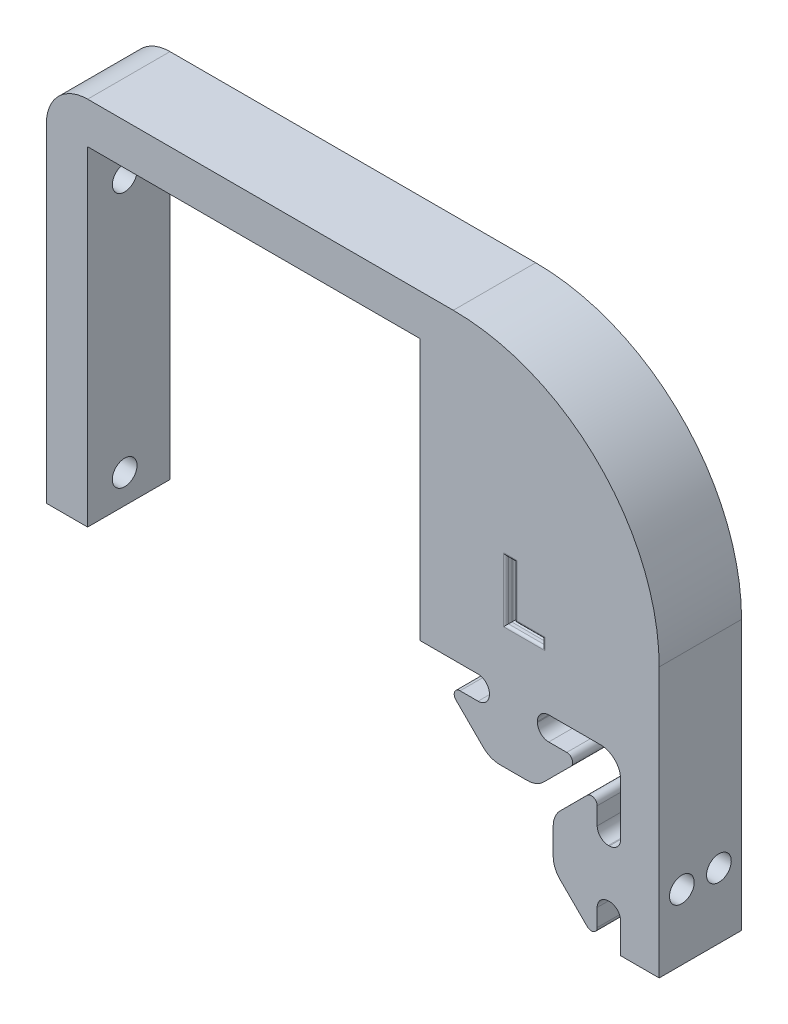
SolidWorks part; units mm, degrees
ref_plane "Front Plane" through (0, 0, 0) normal (0, 0, 1) x (1, 0, 0)
ref_plane "Top Plane" through (0, 0, 0) normal (0, 1, 0) x (1, 0, 0)
ref_plane "Right Plane" through (0, 0, 0) normal (1, 0, 0) x (0, 0, -1)
sketch "Sketch1" plane through (0, 0, 0) normal (0, 0, 1) x (1, 0, 0)
  line L0 (13.02, -7.9417) -> (17.7, -7.9417)
  line L1 (17.7, -7.9417) -> (17.7, 49.77)
  line L2 (17.7, 49.77) -> (-56.7, 49.77)
  line L3 (-14.4742, 2.77) -> (-67.0037, 2.77) construction
  line L4 (-19.4439, 2.77) -> (-19.4439, 44.77) construction
  line L5 (-10.5664, 13.02) -> (-10.5664, 44.77)
  line L6 (-10.5664, 44.77) -> (-51.7, 44.77)
  line L7 (-51.7, 44.77) -> (-51.7, 4.77)
  line L8 (-56.7, 49.77) -> (-56.7, 4.77)
  line L9 (-56.7, 4.77) -> (-51.7, 4.77)
  line L10 (12.7, -6.3331) -> (12.7, -7.9417) construction
  line L11 (13.02, -5.3171) -> (13.02, -4.2875)
  line L12 (11.651, -2.9185) -> (11.5392, -2.9185)
  line L13 (10.1702, -4.2875) -> (10.1702, -6.4021)
  line L14 (8.9631, -6.9029) -> (5.667, -3.6143)
  line L15 (4.8285, -1.5932) -> (4.8285, 1.5932)
  line L16 (5.667, 3.6143) -> (8.9631, 6.9029)
  line L17 (10.1702, 6.4021) -> (10.1702, 4.2875)
  line L18 (11.5392, 2.9185) -> (11.651, 2.9185)
  line L19 (13.02, 10.5773) -> (13.02, 4.2875)
  line L20 (6.3329, 13.02) -> (10.5626, 13.0198)
  line L22 (6.3329, 13.02) -> (4.2875, 13.02)
  line L23 (2.9185, 11.651) -> (2.9185, 11.5392)
  line L24 (4.2875, 10.1702) -> (6.4768, 10.1702)
  line L25 (6.981, 8.9509) -> (3.6723, 5.6497)
  line L26 (1.6558, 4.8158) -> (-1.6558, 4.8158)
  line L27 (-3.6723, 5.6497) -> (-6.981, 8.9509)
  line L28 (-6.4768, 10.1702) -> (-4.2875, 10.1702)
  line L29 (-2.9185, 11.5392) -> (-2.9185, 11.651)
  line L30 (-4.2875, 13.02) -> (-5.3171, 13.02)
  line L31 (-5.3171, 13.02) -> (-10.5664, 13.02)
  line L32 (13.02, -5.3171) -> (13.02, -7.9417)
  line L33 (13.02, -6.3331) -> (13.02, -7.9417) construction
  line L34 (13.02, 4.2875) -> (13.02, 5.3171) construction
  line L37 (5.3171, 13.02) -> (4.2875, 13.02) construction
  line L38 (-6.3331, 13.02) -> (-9.5504, 13.02) construction
  line L96 (12.7, -5.3171) -> (12.7, -4.2875) construction
  line L97 (11.651, -3.2385) -> (11.5392, -3.2385) construction
  line L98 (10.4902, -4.2875) -> (10.4902, -6.4021) construction
  line L99 (8.7371, -7.1294) -> (5.441, -3.8408) construction
  line L100 (4.5085, -1.5932) -> (4.5085, 1.5932) construction
  line L101 (5.441, 3.8408) -> (8.7371, 7.1294) construction
  line L102 (10.4902, 6.4021) -> (10.4902, 4.2875) construction
  line L103 (11.5392, 3.2385) -> (11.651, 3.2385) construction
  line L104 (12.7, 4.2875) -> (12.7, 5.3171) construction
  line L105 (12.7, 6.3331) -> (12.7, 9.5504) construction
  line L106 (9.5504, 12.7) -> (6.3331, 12.7) construction
  line L107 (5.3171, 12.7) -> (4.2875, 12.7) construction
  line L108 (3.2385, 11.651) -> (3.2385, 11.5392) construction
  line L109 (4.2875, 10.4902) -> (6.4768, 10.4902) construction
  line L110 (7.207, 8.7244) -> (3.8983, 5.4232) construction
  line L111 (1.6558, 4.4958) -> (-1.6558, 4.4958) construction
  line L112 (-3.8983, 5.4232) -> (-7.207, 8.7244) construction
  line L113 (-6.4768, 10.4902) -> (-4.2875, 10.4902) construction
  line L114 (-3.2385, 11.5392) -> (-3.2385, 11.651) construction
  line L115 (-4.2875, 12.7) -> (-5.3171, 12.7) construction
  line L116 (-6.3331, 12.7) -> (-9.5504, 12.7) construction
  arc A0 (13.02, -4.2875) -> (11.651, -2.9185) centre (11.651, -4.2875) ccw
  arc A1 (11.5392, -2.9185) -> (10.1702, -4.2875) centre (11.5392, -4.2875) ccw
  arc A2 (8.9631, -6.9029) -> (10.1702, -6.4021) centre (9.4628, -6.4021) ccw
  arc A3 (4.8285, -1.5932) -> (5.667, -3.6143) centre (7.6835, -1.5932) ccw
  arc A4 (5.667, 3.6143) -> (4.8285, 1.5932) centre (7.6835, 1.5932) ccw
  arc A5 (10.1702, 6.4021) -> (8.9631, 6.9029) centre (9.4628, 6.4021) ccw
  arc A6 (10.1702, 4.2875) -> (11.5392, 2.9185) centre (11.5392, 4.2875) ccw
  arc A7 (11.651, 2.9185) -> (13.02, 4.2875) centre (11.651, 4.2875) ccw
  arc A8 (4.2875, 13.02) -> (2.9185, 11.651) centre (4.2875, 11.651) ccw
  arc A9 (2.9185, 11.5392) -> (4.2875, 10.1702) centre (4.2875, 11.5392) ccw
  arc A10 (6.981, 8.9509) -> (6.4768, 10.1702) centre (6.4768, 9.4563) ccw
  arc A11 (1.6558, 4.8158) -> (3.6723, 5.6497) centre (1.6558, 7.6708) ccw
  arc A12 (-3.6723, 5.6497) -> (-1.6558, 4.8158) centre (-1.6558, 7.6708) ccw
  arc A13 (-6.4768, 10.1702) -> (-6.981, 8.9509) centre (-6.4768, 9.4563) ccw
  arc A14 (-4.2875, 10.1702) -> (-2.9185, 11.5392) centre (-4.2875, 11.5392) ccw
  arc A15 (-2.9185, 11.651) -> (-4.2875, 13.02) centre (-4.2875, 11.651) ccw
  arc A16 (13.02, 10.5773) -> (10.5626, 13.0198) centre (10.5918, 10.5918) ccw
  arc A17 (13.0198, 10.5625) -> (10.5626, 13.0198) centre (10.5918, 10.5918) ccw construction
  arc A114 (12.7, -5.3171) -> (12.7, -6.3331) centre (12.7, -5.8251) ccw construction
  arc A115 (12.7, -4.2875) -> (11.651, -3.2385) centre (11.651, -4.2875) ccw construction
  arc A116 (11.5392, -3.2385) -> (10.4902, -4.2875) centre (11.5392, -4.2875) ccw construction
  arc A117 (8.7371, -7.1294) -> (10.4902, -6.4021) centre (9.4628, -6.4021) ccw construction
  arc A118 (4.5085, -1.5932) -> (5.441, -3.8408) centre (7.6835, -1.5932) ccw construction
  arc A119 (5.441, 3.8408) -> (4.5085, 1.5932) centre (7.6835, 1.5932) ccw construction
  arc A120 (10.4902, 6.4021) -> (8.7371, 7.1294) centre (9.4628, 6.4021) ccw construction
  arc A121 (10.4902, 4.2875) -> (11.5392, 3.2385) centre (11.5392, 4.2875) ccw construction
  arc A122 (11.651, 3.2385) -> (12.7, 4.2875) centre (11.651, 4.2875) ccw construction
  arc A123 (12.7, 6.3331) -> (12.7, 5.3171) centre (12.7, 5.8251) ccw construction
  arc A124 (12.6998, 10.5664) -> (12.7, 9.5504) centre (12.7, 10.0584) ccw construction
  arc A125 (12.6998, 10.5664) -> (10.5664, 12.6998) centre (10.5918, 10.5918) ccw construction
  arc A126 (9.5504, 12.7) -> (10.5664, 12.6998) centre (10.0584, 12.7) ccw construction
  arc A127 (5.3171, 12.7) -> (6.3331, 12.7) centre (5.8251, 12.7) ccw construction
  arc A128 (4.2875, 12.7) -> (3.2385, 11.651) centre (4.2875, 11.651) ccw construction
  arc A129 (3.2385, 11.5392) -> (4.2875, 10.4902) centre (4.2875, 11.5392) ccw construction
  arc A130 (7.207, 8.7244) -> (6.4768, 10.4902) centre (6.4768, 9.4563) ccw construction
  arc A131 (1.6558, 4.4958) -> (3.8983, 5.4232) centre (1.6558, 7.6708) ccw construction
  arc A132 (-3.8983, 5.4232) -> (-1.6558, 4.4958) centre (-1.6558, 7.6708) ccw construction
  arc A133 (-6.4768, 10.4902) -> (-7.207, 8.7244) centre (-6.4768, 9.4563) ccw construction
  arc A134 (-4.2875, 10.4902) -> (-3.2385, 11.5392) centre (-4.2875, 11.5392) ccw construction
  arc A135 (-3.2385, 11.651) -> (-4.2875, 12.7) centre (-4.2875, 11.651) ccw construction
  arc A136 (-6.3331, 12.7) -> (-5.3171, 12.7) centre (-5.8251, 12.7) ccw construction
  arc A137 (-10.5664, 12.6998) -> (-9.5504, 12.7) centre (-10.0584, 12.7) ccw construction
  dimension "D1" = 47
  dimension "D2" = 74.4
  dimension "D3" = 5
  dimension "D4" = 5
  dimension "D5" = 40
  dimension "D6" = 5
  dimension "D8" = 0.32
  dimension "D7" = 6.2898
  dimension "D9" = 4.2297
  dimension "D11" = 57.7117
extrude "Boss-Extrude1" add sketch "Sketch1" along normal blind 10
sketch "Sketch2" plane through (-56.7, 0, 0) normal (-1, 0, 0) x (0, 0, 1)
  line L1 (10, 49.77) -> (0, 49.77) construction
  line L2 (10, 29.3002) -> (10, 4.77) construction
  line L7 (5.5, 39.27) -> (5.5, 8.27) construction
  circle A0 centre (5.5, 8.27) radius 1.5
  circle A1 centre (5.5, 39.27) radius 1.5
  dimension "D3" = 3
  dimension "D4" = 3
  dimension "D1" = 4.5
  dimension "D2" = 31
  dimension "D5" = 10.5
extrude "Cut-Extrude1" cut sketch "Sketch2" against normal up to next
fillet "Fillet3" radius 5 1 edges at (-56.7, 49.77, 5)
sketch "Sketch3" plane through (17.7, 0, 0) normal (1, 0, 0) x (0, 0, -1)
  line L0 (-5, 1.5932) -> (-5, -1.5932) construction
  line L1 (-10, 0) -> (0, 0) construction
  line L4 (0, -1.5932) -> (0, 1.5932)
  line L5 (-10, -1.5932) -> (0, -1.5932)
  line L6 (-10, 1.5932) -> (-10, -1.5932)
  line L7 (0, 1.5932) -> (-10, 1.5932)
  line L12 (0, -1.5932) -> (0, 1.5932) construction
  line L13 (-10, -1.5932) -> (0, -1.5932) construction
  line L14 (-10, 1.5932) -> (-10, -1.5932) construction
  line L15 (0, 1.5932) -> (-10, 1.5932) construction
  circle A0 centre (-7.25, 0) radius 1.5
  circle A1 centre (-2.75, 0) radius 1.5
  dimension "D4" = 2.25
  dimension "D2" = 3
  dimension "D3" = 2.25
  dimension "D1" = 0
extrude "Cut-Extrude2" cut sketch "Sketch3" against normal up to next contours A1 | A0
fillet "Fillet4" radius 25 1 edges at (17.7, 49.77, 5)
sketch "Sketch7" plane through (0, 0, 10) normal (0, 0, 1) x (1, 0, 0)
  text T0 "L" font "Arial" height in points 28
extrude "Cut-Extrude7" cut sketch "Sketch7" against normal blind 1
fillet "Fillet8" radius 0.3 12 edges at (-0.901, 23.4386, 9) (-0.3939, 27.0343, 9) (0.1132, 23.8535, 9) (1.8188, 20.6728, 9) (3.5244, 20.2579, 9) (1.3117, 19.843, 9) (1.3117, 19.843, 10) (3.5244, 20.2579, 10) (1.8188, 20.6728, 10) (0.1132, 23.8535, 10) (-0.3939, 27.0343, 10) (-0.901, 23.4386, 10)
sketch "Sketch8" plane through (-10.5664, 0, 0) normal (-1, 0, 0) x (0, 0, 1)
  line L4 (0, 44.77) -> (0, 13.02)
  line L5 (0, 13.02) -> (10, 13.02)
  line L6 (10, 13.02) -> (10, 44.77)
  line L7 (10, 44.77) -> (0, 44.77)
  line L8 (0, 44.77) -> (0, 13.02)
  line L9 (0, 13.02) -> (10, 13.02)
  line L10 (10, 13.02) -> (10, 44.77)
  line L11 (10, 44.77) -> (0, 44.77)
  dimension "D1" = 0
extrude "Boss-Extrude2" add sketch "Sketch8" along normal blind 0.8
